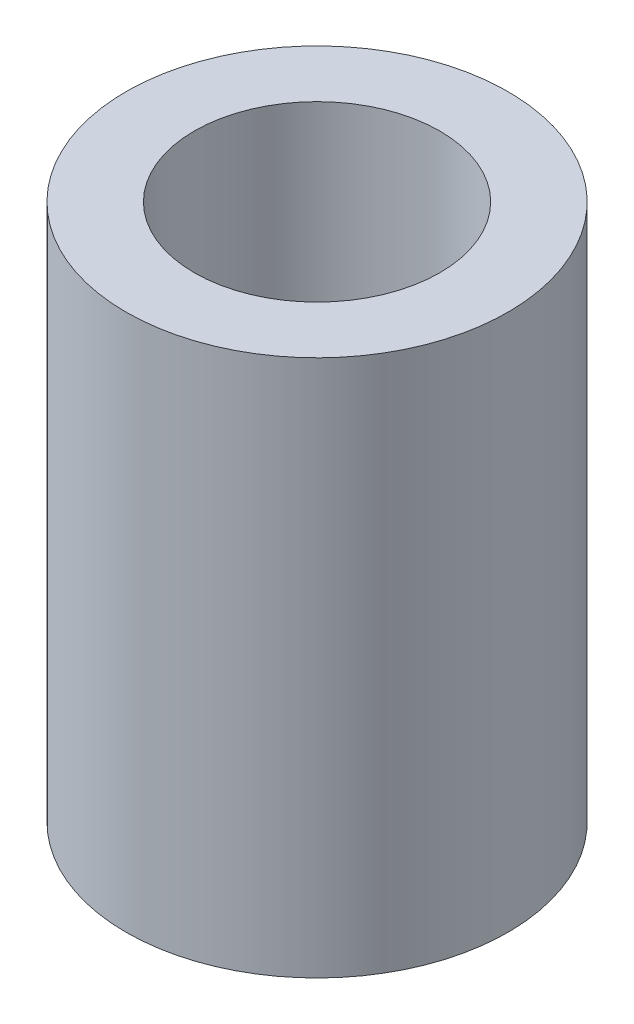
SolidWorks part; units mm, degrees
ref_plane "Front Plane" through (0, 0, 0) normal (0, 0, 1) x (1, 0, 0)
ref_plane "Top Plane" through (0, 0, 0) normal (0, 1, 0) x (1, 0, 0)
ref_plane "Right Plane" through (0, 0, 0) normal (1, 0, 0) x (0, 0, -1)
sketch "Sketch1" plane through (0, 0, 0) normal (0, 1, 0) x (1, 0, 0)
  circle A1 centre (0, 0) radius 3.556
extrude "Boss-Extrude1" add sketch "Sketch1" along normal blind 10
sketch "Sketch2" plane through (0, 10, 0) normal (0, 1, 0) x (1, 0, 0)
  circle A0 centre (0, 0) radius 1.905 construction
  circle A1 centre (0, 0) radius 2.286
  point P4 (-11.2657, -1.1834)
extrude "Cut-Extrude1" cut sketch "Sketch2" against normal blind 7.5
